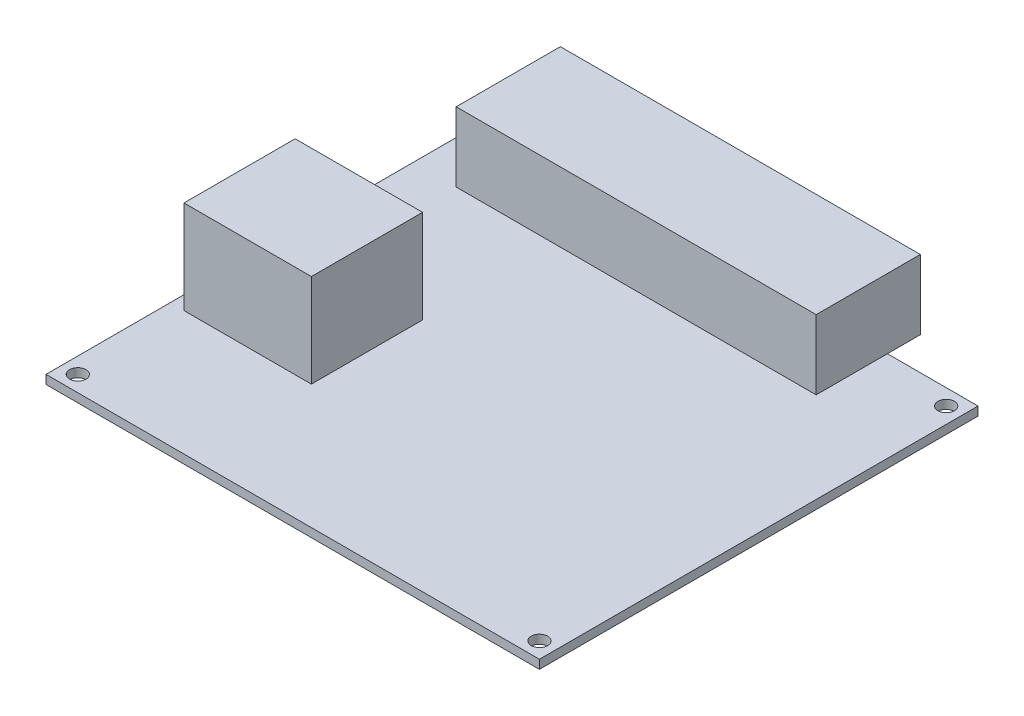
SolidWorks part; units mm, degrees
ref_plane "Front Plane" through (0, 0, 0) normal (0, 0, 1) x (1, 0, 0)
ref_plane "Top Plane" through (0, 0, 0) normal (0, 1, 0) x (1, 0, 0)
ref_plane "Right Plane" through (0, 0, 0) normal (1, 0, 0) x (0, 0, -1)
sketch "Sketch1" plane through (0, 0, 0) normal (0, 1, 0) x (1, 0, 0)
  line L4 (-42.1, 40) -> (-42.1, 38.6) construction
  line L5 (-45, -40) -> (45, -40)
  line L6 (-45, -40) -> (-45, 40)
  line L7 (-45, 40) -> (45, 40)
  line L8 (45, -40) -> (45, 40)
  line L9 (-45, -40) -> (45, 40) construction
  line L10 (-45, 40) -> (45, -40) construction
  line L11 (-45, 37.1) -> (-43.6, 37.1) construction
  line L12 (0, -44) -> (0, 44) construction
  line L13 (-49.5, 0) -> (49.5, 0) construction
  circle A0 centre (-42.1, 37.1) radius 1.5
  circle A1 centre (42.1, 37.1) radius 1.5
  circle A2 centre (-42.1, -37.1) radius 1.5
  circle A3 centre (42.1, -37.1) radius 1.5
  point P0 (0, 0)
  point P12 (-41.4327, 38.6)
  point P13 (-42.1319, 37.4506)
  point P14 (-41.677, 36.9844)
  point P15 (-41.677, 38.5462)
  point P16 (-43.6, 37.1)
  point P17 (-41.7375, 37.1)
  point P18 (-41.7925, 37.1489)
  point P19 (-43.6, 37.1)
  point P20 (0, 0)
  point P21 (-42.0107, 37.1)
  point P22 (-43.6, 37.0954)
  point P23 (-42.253, 37.0954)
  point P24 (-43.6, 36.9257)
  point P25 (-43.753, 37.1)
  dimension "D5" = 3
  dimension "D1" = 80
  dimension "D2" = 90
  dimension "D3" = 1.4
  dimension "D4" = 1.4
extrude "Boss-Extrude2" add sketch "Sketch1" along normal blind 1.6
sketch "Sketch2" plane through (0, 1.6, 0) normal (0, 1, 0) x (1, 0, 0)
  line L0 (-37.18, 46) -> (28.48, 46)
  line L1 (28.48, 46) -> (28.48, 27)
  line L2 (28.48, 27) -> (-37.18, 27)
  line L3 (-37.18, 27) -> (-37.18, 46)
  line L4 (40.6, 40) -> (40.6, 37.1) construction
  line L5 (45, 40) -> (-45, 40) construction
  line L6 (40.6, 37.1) -> (42.1, 37.1) construction
  circle A1 centre (42.1, 37.1) radius 1.5 construction
  dimension "D1" = 65.66
  dimension "D2" = 12.12
  dimension "D3" = 19
  dimension "D4" = 6
extrude "Boss-Extrude3" add sketch "Sketch2" along normal blind 12.68
sketch "Sketch3" plane through (0, 1.6, 0) normal (0, 1, 0) x (1, 0, 0)
  line L0 (-45, -40) -> (45, -40) construction
  line L1 (-42.4945, -17.3394) -> (-19.2535, -17.3394)
  line L2 (-42.4945, -17.3394) -> (-42.4945, 2.9394)
  line L3 (-42.4945, 2.9394) -> (-19.2535, 2.9394)
  line L4 (-19.2535, -17.3394) -> (-19.2535, 2.9394)
  line L5 (-42.4945, -17.3394) -> (-19.2535, 2.9394) construction
  line L6 (-42.4945, 2.9394) -> (-19.2535, -17.3394) construction
  point P0 (-30.874, -7.2)
  dimension "D1" = 32.8
  dimension "D2" = 23.2409
extrude "Boss-Extrude4" add sketch "Sketch3" along normal blind 17
